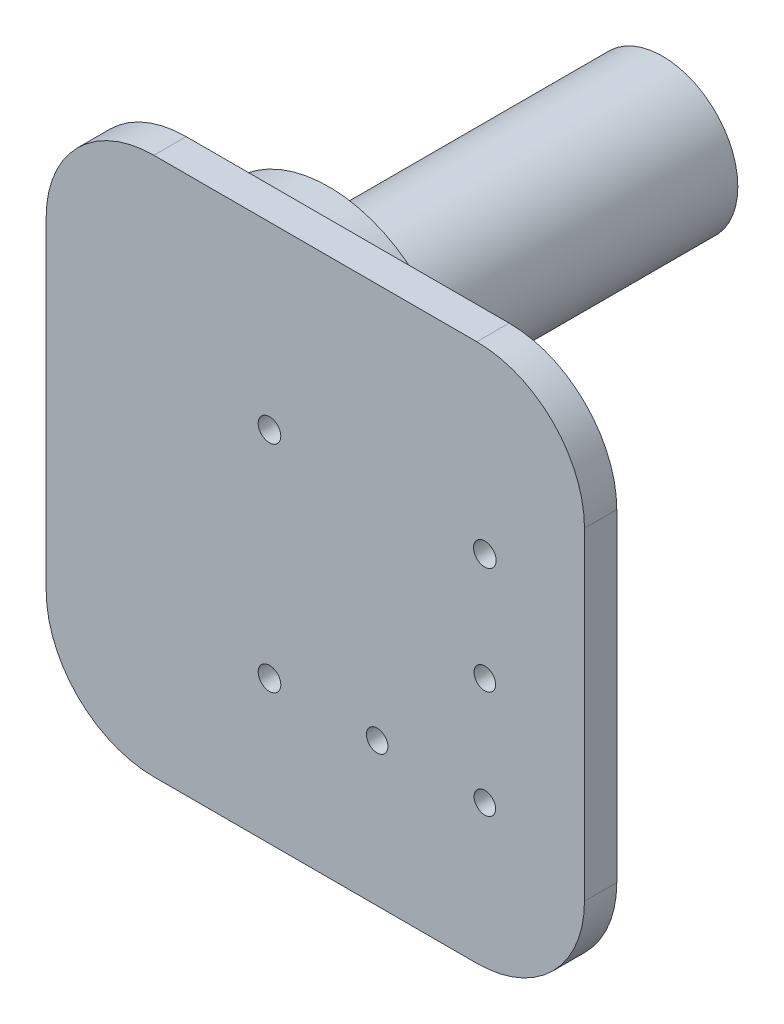
SolidWorks part; units mm, degrees
ref_plane "前视基准面" through (0, 0, 0) normal (0, 0, 1) x (1, 0, 0)
ref_plane "上视基准面" through (0, 0, 0) normal (0, 1, 0) x (1, 0, 0)
ref_plane "右视基准面" through (0, 0, 0) normal (1, 0, 0) x (0, 0, -1)
other "Configuration Table"
sketch "草图1" plane through (0, 0, 0) normal (0, 0, 1) x (1, 0, 0)
  circle A0 centre (-86.6066, -63.7835) radius 7
extrude "凸台-拉伸1" add sketch "草图1" along normal blind 34
sketch "草图2" plane through (0, 0, 34) normal (0, 0, 1) x (1, 0, 0)
  circle A0 centre (-86.6066, -63.7835) radius 12
extrude "凸台-拉伸2" add sketch "草图2" against normal blind 3 and the other way blind 2
sketch "草图3" plane through (0, 0, 36) normal (0, 0, 1) x (1, 0, 0)
  line L0 (-110.1056, -28.4593) -> (-40.7849, -42.3949) construction
  line L3 (-104.8495, -49.3813) -> (-54.8495, -49.3813)
  line L4 (-104.8495, -49.3813) -> (-104.8495, -99.3813)
  line L5 (-54.8495, -49.3813) -> (-54.8495, -99.3813)
  line L6 (-104.8495, -99.3813) -> (-54.8495, -99.3813)
  arc A0 (-125.6196, -54.9524) -> (-91.6831, -24.107) centre (-86.6066, -63.7835) ccw construction
extrude "凸台-拉伸4" add sketch "草图3" along normal blind 3
sketch "草图5" plane through (0, 0, 39) normal (0, 0, 1) x (1, 0, 0)
  circle A0 centre (-84.1066, -86.0879) radius 1.05
  circle A4 centre (-74.1066, -86.0879) radius 1
  circle A5 centre (-64.1066, -86.0879) radius 1
  circle A6 centre (-64.1066, -76.0879) radius 1
  circle A7 centre (-64.1066, -66.0879) radius 1.05
  circle A8 centre (-84.1066, -66.0879) radius 1.05
extrude "切除-拉伸1" cut sketch "草图5" against normal blind 5
fillet "圆角1" radius 10 4 edges at (-104.8495, -99.3813, 37.5) (-54.8495, -99.3813, 37.5) (-54.8495, -49.3813, 37.5) (-104.8495, -49.3813, 37.5)
